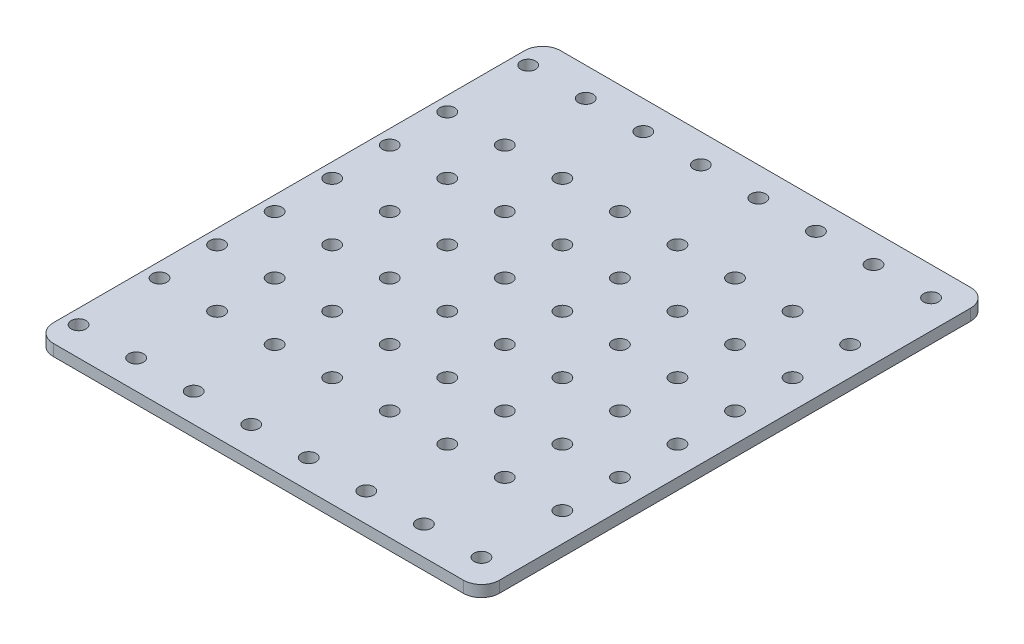
SolidWorks part; units mm, degrees
ref_plane "Front Plane" through (0, 0, 0) normal (0, 0, 1) x (1, 0, 0)
ref_plane "Top Plane" through (0, 0, 0) normal (0, 1, 0) x (1, 0, 0)
ref_plane "Right Plane" through (0, 0, 0) normal (1, 0, 0) x (0, 0, -1)
sketch "Sketch1" plane through (0, 0, 0) normal (0, 1, 0) x (1, 0, 0)
  line L0 (0, 0) -> (50000, 0) construction
  line L1 (62, 70.5) -> (-62, 70.5)
  line L2 (62, 70.5) -> (62, -70.5)
  line L3 (62, -70.5) -> (-62, -70.5)
  line L4 (-62, 70.5) -> (-62, -70.5)
  line L5 (62, 70.5) -> (-62, -70.5) construction
  line L6 (62, -70.5) -> (-62, 70.5) construction
  line L7 (0, 0) -> (0, 50000) construction
  line L8 (-23.2534, -62.5) -> (49976.7466, -62.5) construction
  line L9 (-58, -36.0262) -> (-58, -50036.0262) construction
  line L10 (-11.274, -56) -> (49988.726, -56) construction
  line L11 (54, -56) -> (38, -56) construction
  circle A0 centre (-58, -62.5) radius 2.05
  circle A2 centre (-42, -62.5) radius 2.05
  circle A3 centre (-26, -62.5) radius 2.05
  circle A4 centre (-10, -62.5) radius 2.05
  circle A5 centre (6, -62.5) radius 2.05
  circle A6 centre (22, -62.5) radius 2.05
  circle A7 centre (38, -62.5) radius 2.05
  circle A8 centre (54, -62.5) radius 2.05
  circle A9 centre (54, -56) radius 2.05 construction
  circle A10 centre (38, -56) radius 2.05 construction
  circle A11 centre (22, -56) radius 2.05 construction
  circle A12 centre (6, -56) radius 2.05 construction
  circle A13 centre (-10, -56) radius 2.05 construction
  circle A14 centre (-26, -56) radius 2.05 construction
  circle A15 centre (-42, -56) radius 2.05 construction
  circle A16 centre (-58, -56) radius 2.05 construction
  circle A17 centre (38, -40) radius 2.05
  circle A18 centre (22, -40) radius 2.05
  circle A19 centre (6, -40) radius 2.05
  circle A20 centre (-10, -40) radius 2.05
  circle A21 centre (-26, -40) radius 2.05
  circle A22 centre (-42, -40) radius 2.05
  circle A23 centre (-58, -40) radius 2.05
  circle A24 centre (38, -24) radius 2.05
  circle A25 centre (22, -24) radius 2.05
  circle A26 centre (6, -24) radius 2.05
  circle A27 centre (-10, -24) radius 2.05
  circle A28 centre (-26, -24) radius 2.05
  circle A29 centre (-42, -24) radius 2.05
  circle A30 centre (-58, -24) radius 2.05
  circle A31 centre (38, -8) radius 2.05
  circle A32 centre (22, -8) radius 2.05
  circle A33 centre (6, -8) radius 2.05
  circle A34 centre (-10, -8) radius 2.05
  circle A35 centre (-26, -8) radius 2.05
  circle A36 centre (-42, -8) radius 2.05
  circle A37 centre (-58, -8) radius 2.05
  circle A38 centre (38, 8) radius 2.05
  circle A39 centre (22, 8) radius 2.05
  circle A40 centre (6, 8) radius 2.05
  circle A41 centre (-10, 8) radius 2.05
  circle A42 centre (-26, 8) radius 2.05
  circle A43 centre (-42, 8) radius 2.05
  circle A44 centre (-58, 8) radius 2.05
  circle A45 centre (38, 24) radius 2.05
  circle A46 centre (22, 24) radius 2.05
  circle A47 centre (6, 24) radius 2.05
  circle A48 centre (-10, 24) radius 2.05
  circle A49 centre (-26, 24) radius 2.05
  circle A50 centre (-42, 24) radius 2.05
  circle A51 centre (-58, 24) radius 2.05
  circle A52 centre (38, 40) radius 2.05
  circle A53 centre (22, 40) radius 2.05
  circle A54 centre (6, 40) radius 2.05
  circle A55 centre (-10, 40) radius 2.05
  circle A56 centre (-26, 40) radius 2.05
  circle A57 centre (-42, 40) radius 2.05
  circle A58 centre (-58, 40) radius 2.05
  circle A59 centre (38, 56) radius 2.05 construction
  circle A60 centre (22, 56) radius 2.05 construction
  circle A61 centre (6, 56) radius 2.05 construction
  circle A62 centre (-10, 56) radius 2.05 construction
  circle A63 centre (-26, 56) radius 2.05 construction
  circle A64 centre (-42, 56) radius 2.05 construction
  circle A65 centre (-58, 56) radius 2.05 construction
  circle A66 centre (54, -40) radius 2.05
  circle A67 centre (54, -24) radius 2.05
  circle A68 centre (54, -8) radius 2.05
  circle A69 centre (54, 8) radius 2.05
  circle A70 centre (54, 24) radius 2.05
  circle A71 centre (54, 40) radius 2.05
  circle A72 centre (54, 56) radius 2.05 construction
  circle A73 centre (-58, 62.5) radius 2.05
  circle A74 centre (-42, 62.5) radius 2.05
  circle A75 centre (-26, 62.5) radius 2.05
  circle A76 centre (-10, 62.5) radius 2.05
  circle A77 centre (6, 62.5) radius 2.05
  circle A78 centre (22, 62.5) radius 2.05
  circle A79 centre (38, 62.5) radius 2.05
  circle A80 centre (54, 62.5) radius 2.05
  point P0 (0, 0)
  dimension "D5" = 4.1
  dimension "D1" = 124
  dimension "D2" = 141
  dimension "D3" = 4
  dimension "D4" = 8
  dimension "D7" = 8
  dimension "D8" = 6.5
  dimension "D11" = 16
  dimension "D12" = 8
  dimension "D6" = 8
  dimension "D9" = 8
  dimension "D10" = 8
extrude "Boss-Extrude1" add sketch "Sketch1" along normal blind 3.175
fillet "Fillet1" radius 5 4 edges at (-62, 1.5875, -70.5) (62, 1.5875, -70.5) (62, 1.5875, 70.5) (-62, 1.5875, 70.5)
equation "\"h\"= 141mm"
equation "\"w\"= 15 * 8 + 4mm"
equation "\"D1@Sketch1\"=\"w\""
equation "\"D2@Sketch1\"=\"h\""
